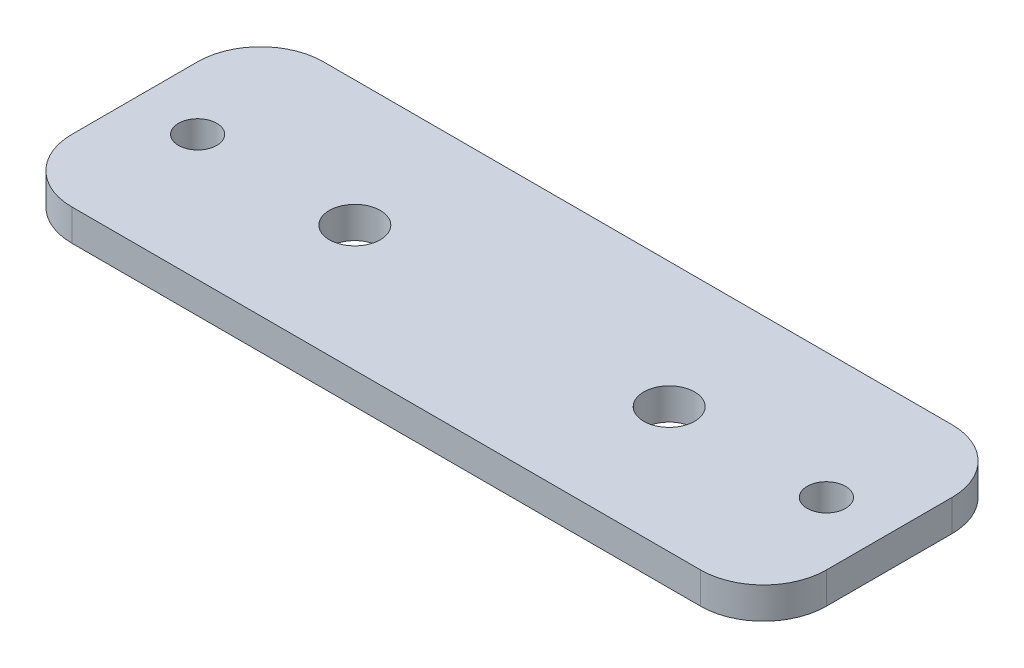
SolidWorks part; units mm, degrees
ref_plane "Front Plane" through (0, 0, 0) normal (0, 0, 1) x (1, 0, 0)
ref_plane "Top Plane" through (0, 0, 0) normal (0, 1, 0) x (1, 0, 0)
ref_plane "Right Plane" through (0, 0, 0) normal (1, 0, 0) x (0, 0, -1)
sketch "Sketch1" plane through (0, 0, 0) normal (0, 1, 0) x (1, 0, 0)
  line L1 (-60, 20) -> (60, 20)
  line L2 (-60, 20) -> (-60, -20)
  line L3 (-60, -20) -> (60, -20)
  line L4 (60, 20) -> (60, -20)
  line L5 (-60, 20) -> (60, -20) construction
  line L6 (-60, -20) -> (60, 20) construction
  point P0 (0, 0)
  dimension "D1" = 40
  dimension "D2" = 120
extrude "Boss-Extrude1" add sketch "Sketch1" along normal blind 5
sketch "Sketch2" plane through (0, 5, 0) normal (0, 1, 0) x (1, 0, 0)
  line L0 (-60, 0) -> (60, 0) construction
  line L1 (-60, 20) -> (-60, -20) construction
  line L2 (60, -20) -> (60, 20) construction
  circle A0 centre (-25, 0) radius 4.05
  circle A1 centre (-50, 0) radius 3.05
  dimension "D1" = 8.1
  dimension "D4" = 6.1
  dimension "D2" = 25
  dimension "D3" = 50
extrude "Cut-Extrude1" cut sketch "Sketch2" against normal through all contours A0 | A1
mirror "Mirror1" about plane through (0, 0, 0) normal (1, 0, 0) of "Cut-Extrude1"
fillet "Fillet1" radius 10 4 edges at (-60, 2.5, -20) (-60, 2.5, 20) (60, 2.5, -20) (60, 2.5, 20)
